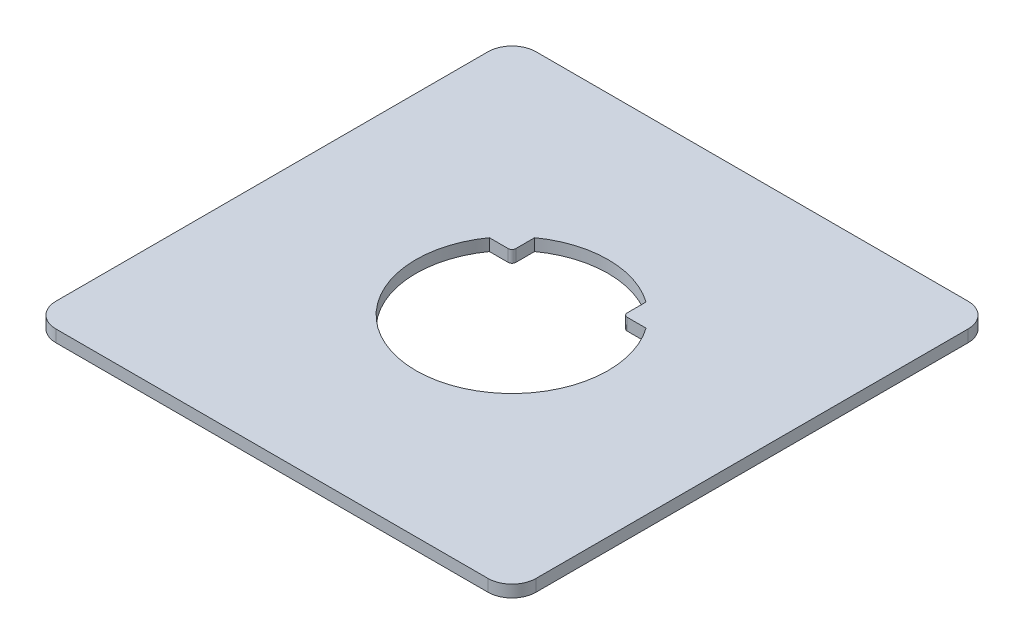
SolidWorks part; units mm, degrees
ref_plane "Front Plane" through (0, 0, 0) normal (0, 0, 1) x (1, 0, 0)
ref_plane "Top Plane" through (0, 0, 0) normal (0, 1, 0) x (1, 0, 0)
ref_plane "Right Plane" through (0, 0, 0) normal (1, 0, 0) x (0, 0, -1)
sketch "Sketch1" plane through (0, 0, 0) normal (0, 1, 0) x (1, 0, 0)
  line L0 (24.384, 42.1112) -> (24.384, 39.116)
  line L1 (0, 0) -> (63.5, 0)
  line L2 (0, 0) -> (0, 63.5)
  line L3 (0, 63.5) -> (63.5, 63.5)
  line L4 (63.5, 0) -> (63.5, 63.5)
  line L5 (24.384, 39.116) -> (21.3888, 39.116)
  line L6 (39.116, 42.1112) -> (39.116, 39.116)
  line L7 (39.116, 39.116) -> (42.1112, 39.116)
  arc A0 (21.3888, 39.116) -> (42.1112, 39.116) centre (31.75, 31.75) ccw
  arc A1 (39.116, 42.1112) -> (24.384, 42.1112) centre (31.75, 31.75) ccw
  point P7 (31.75, 0)
  point P8 (0, 31.75)
  dimension "D2" = 25.4254
  dimension "D1" = 63.5
  dimension "D3" = 14.732
extrude "Boss-Extrude1" add sketch "Sketch1" along normal blind 1.5875
fillet "Fillet1" radius 0.508 2 edges at (39.116, 0.7937, -39.116) (24.384, 0.7937, -39.116)
fillet "Fillet2" radius 3.175 4 edges at (63.5, 0.7937, 0) (63.5, 0.7937, -63.5) (0, 0.7937, -63.5) (0, 0.7937, 0)
